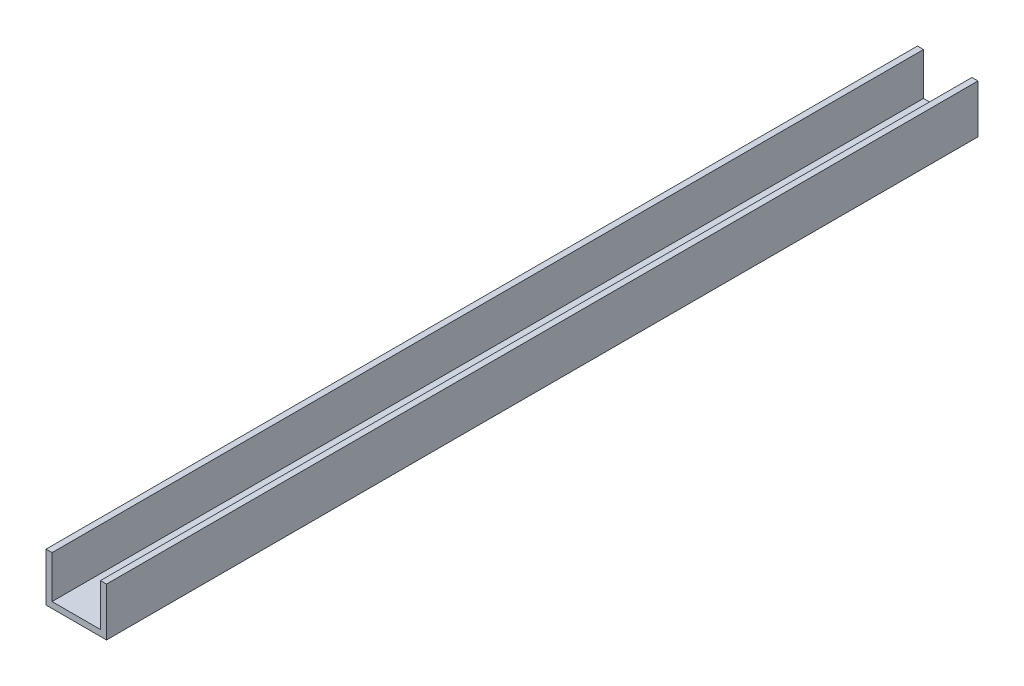
SolidWorks part; units mm, degrees
ref_plane "Front" through (0, 0, 0) normal (0, 0, 1) x (1, 0, 0)
ref_plane "Top" through (0, 0, 0) normal (0, 1, 0) x (1, 0, 0)
ref_plane "Right" through (0, 0, 0) normal (1, 0, 0) x (0, 0, -1)
sketch "Sketch1" plane through (0, 0, 0) normal (0, 0, 1) x (1, 0, 0)
  line L0 (0, -12.7) -> (0, 12.7) construction
  line L1 (-15.875, 0) -> (15.875, 0) construction
  line L2 (12.7, 12.7) -> (-12.7, 12.7) construction
  line L3 (-15.875, -12.7) -> (15.875, -12.7)
  line L4 (-15.875, -12.7) -> (-15.875, 12.7)
  line L5 (-15.875, 12.7) -> (15.875, 12.7)
  line L6 (15.875, -12.7) -> (15.875, 12.7)
  line L7 (-15.875, -12.7) -> (15.875, 12.7) construction
  line L8 (-15.875, 12.7) -> (15.875, -12.7) construction
  line L9 (-12.7, -12.7) -> (12.7, -12.7)
  point P3 (0, 0)
  point P4 (0, 0)
  point P8 (0, 0)
  point P13 (15.875, -9.525)
  point P17 (0, 12.7)
  point P20 (0, -12.7)
  dimension "Outside Width" = 31.75
  dimension "Outside Height" = 25.4
  dimension "Inside Height" = 22.225
  dimension "Wall Thickness" = 3.175
  dimension "Inside Width" = 25.4
sketch "Sketch2" plane through (0, 0, 0) normal (1, 0, 0) x (0, 0, -1)
  line L0 (-609.6, 0) -> (609.6, 0) construction
  dimension "Length" = 1219.2
sketch "Sketch3" plane through (0, 0, 0) normal (0, 0, 1) x (1, 0, 0)
  line L0 (-15.875, 12.7) -> (-15.875, -12.7)
  line L1 (-15.875, -12.7) -> (15.875, -12.7)
  line L2 (15.875, -12.7) -> (15.875, 12.7)
  line L3 (15.875, 12.7) -> (12.7, 12.7)
  line L4 (12.7, 12.7) -> (12.7, -9.525)
  line L5 (12.7, -9.525) -> (-12.7, -9.525)
  line L6 (-12.7, -9.525) -> (-12.7, 12.7)
  line L7 (-12.7, 12.7) -> (-15.875, 12.7)
  line L8 (-12.7, -9.525) -> (-12.7, -12.7) construction
  dimension "D1" = 25.4
  dimension "D2" = 31.75
  dimension "D3" = 3.175
extrude "Boss-Extrude2" add sketch "Sketch3" along normal mid plane 1219.2
sketch "Reference Sketch1" plane through (0, 0, 0) normal (1, 0, 0) x (0, 0, -1)
  line L0 (-609.6, 0) -> (609.6, 0) construction
  point P0 (-565.15, 0)
  point P1 (565.15, 0)
  dimension "D1" = 44.45
  dimension "D2" = 44.45
ref_plane "Plane1" through (12.7, -9.525, 609.6) normal (0, -1, 0) x (-1, 0, 0)
sketch "Sketch5" plane through (0, 0, 609.6) normal (0, 0, 1) x (1, 0, 0)
  line L0 (-15.875, 12.7) -> (-12.7, 12.7)
  line L1 (-12.7, 12.7) -> (-12.7, -9.525)
  line L2 (-12.7, -9.525) -> (12.7, -9.525)
  line L3 (12.7, -9.525) -> (12.7, 12.7)
  line L4 (12.7, 12.7) -> (15.875, 12.7)
  line L5 (15.875, 12.7) -> (15.875, -12.7)
  line L6 (15.875, -12.7) -> (-15.875, -12.7)
  line L7 (-15.875, -12.7) -> (-15.875, 12.7)
extrude "Cut-Extrude1" cut sketch "Sketch5" against normal blind 1016
sketch "Sketch6" plane through (0, -9.525, 0) normal (0, 1, 0) x (1, 0, 0)
  line L1 (12.7, 406.4) -> (12.7, 609.6) construction
  line L2 (12.7, 406.4) -> (-12.7, 406.4) construction
  point P0 (0, 594.6)
  dimension "D2" = 12.7
  dimension "D3" = 188.2
hole_wizard "M6 Clearance Hole1" positions "Sketch6" profile "Sketch7" hole size "M6" standard "ANSI Metric" end condition through all
sketch "Sketch7" plane through (0, -9.525, -594.6) normal (1, 0, 0) x (0, 0, 1)
  line L0 (0, 0) -> (0, 3.175)
  line L1 (0, 3.175) -> (3.2, 3.175)
  line L2 (3.2, 3.175) -> (3.2, 0)
  line L5 (3.2, 0) -> (0, 0)
  line L11 (0, -6.35) -> (0, 107.95) construction
  dimension "Thru Hole Dia." = 6.4
  dimension "Thru Hole Depth" = 3.175
sketch "Sketch8" plane through (0, 0, -609.6) normal (0, 0, -1) x (-1, 0, 0)
  line L0 (-15.875, 12.7) -> (-12.7, 12.7)
  line L1 (-12.7, 12.7) -> (-12.7, -9.525)
  line L2 (-12.7, -9.525) -> (12.7, -9.525)
  line L3 (12.7, -9.525) -> (12.7, 12.7)
  line L4 (12.7, 12.7) -> (15.875, 12.7)
  line L5 (15.875, 12.7) -> (15.875, -12.7)
  line L6 (15.875, -12.7) -> (-15.875, -12.7)
  line L7 (-15.875, -12.7) -> (-15.875, 12.7)
extrude "Boss-Extrude3" add sketch "Sketch8" along normal blind 254
equation "\"D1@Sketch3\" = \"Outside Height@Sketch1\""
equation "\"D2@Sketch3\" = \"Outside Width@Sketch1\""
equation "\"D3@Sketch3\" = \"Wall Thickness@Sketch1\""
equation "\"D1@Reference Sketch1\"=\"Outside Height@Sketch1\" * 1.75"
equation "\"D2@Reference Sketch1\" = \"D1@Reference Sketch1\""
equation "\"D1@Boss-Extrude2\" = \"Length@Sketch2\""
equation "\"Inside Height@Sketch1\"=\"Outside Height@Sketch1\"-\"Wall Thickness@Sketch1\""
equation "\"Inside Width@Sketch1\"=\"Outside Width@Sketch1\"-\"Wall Thickness@Sketch1\"*2"
